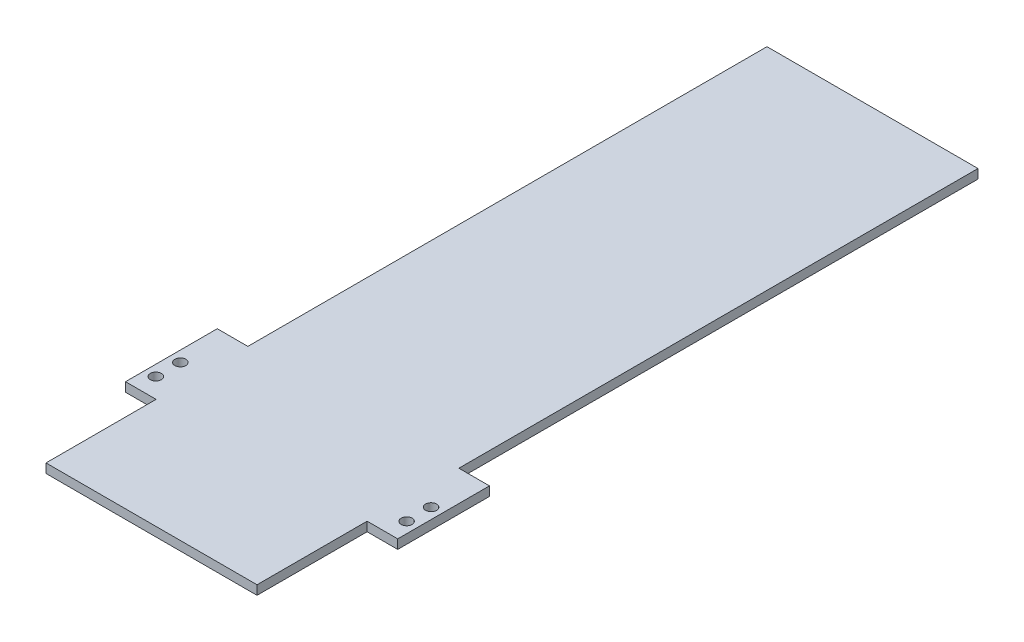
SolidWorks part; units mm, degrees
ref_plane "Front Plane" through (0, 0, 0) normal (0, 0, 1) x (1, 0, 0)
ref_plane "Top Plane" through (0, 0, 0) normal (0, 1, 0) x (1, 0, 0)
ref_plane "Right Plane" through (0, 0, 0) normal (1, 0, 0) x (0, 0, -1)
sketch "Sketch5" plane through (0, 0, 0) normal (0, 1, 0) x (1, 0, 0)
  line L0 (69, 36) -> (79, 36)
  line L1 (0, 0) -> (69, 0)
  line L2 (0, 0) -> (0, 235.74)
  line L3 (0, 235.74) -> (69, 235.74)
  line L4 (69, 0) -> (69, 235.74)
  line L5 (79, 36) -> (79, 66)
  line L6 (79, 66) -> (69, 66)
  line L7 (34.5, 235.74) -> (34.5, 0) construction
  line L8 (-10, 66) -> (0, 66)
  line L9 (-10, 36) -> (-10, 66)
  line L10 (0, 36) -> (-10, 36)
  dimension "D1" = 235.74
  dimension "D2" = 69
  dimension "D3" = 36
  dimension "D4" = 30
  dimension "D5" = 10
extrude "Boss-Extrude5" add sketch "Sketch5" along normal blind 3 contours L10 L2 L8 L9 | L7 L3 L2 L1 | L3 L7 L1 L4 | L5 L6 L4 L0
sketch "Sketch6" plane through (0, 3, 0) normal (0, 1, 0) x (1, 0, 0)
  point P0 (75.5, 50.4206)
  point P3 (75.5, 42.4206)
hole_wizard "M3 Clearance Hole1" positions "Sketch6" profile "Sketch7" hole size "M3" standard "ANSI Metric" end condition through all
sketch "Sketch7" plane through (75.5, 3, -50.4206) normal (1, 0, 0) x (0, 0, 1)
  line L0 (0, 0) -> (0, 3)
  line L1 (0, 3) -> (1.8, 3)
  line L2 (1.8, 3) -> (1.8, 0)
  line L5 (1.8, 0) -> (0, 0)
  line L11 (0, -6.35) -> (0, 107.95) construction
  dimension "Thru Hole Dia." = 3.6
  dimension "Thru Hole Depth" = 3
ref_plane "Plane1" through (34.5, 0, 0) normal (1, 0, 0) x (0, 0, -1)
mirror "Mirror1" about plane through (34.5, 0, 0) normal (1, 0, 0) of "M3 Clearance Hole1"
